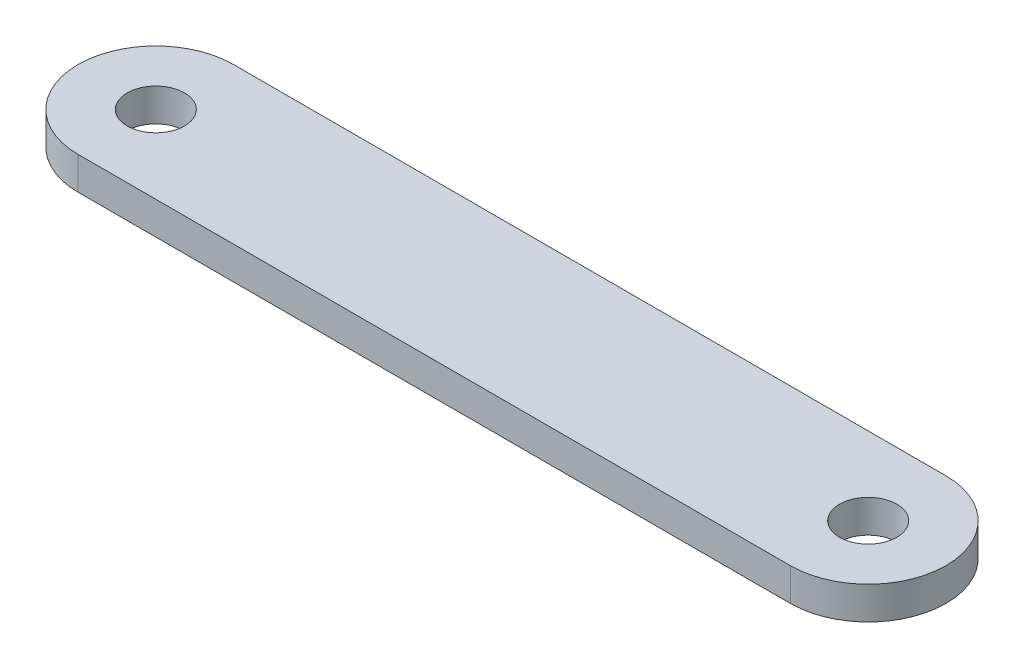
SolidWorks part; units mm, degrees
ref_plane "Front Plane" through (0, 0, 0) normal (0, 0, 1) x (1, 0, 0)
ref_plane "Top Plane" through (0, 0, 0) normal (0, 1, 0) x (1, 0, 0)
ref_plane "Right Plane" through (0, 0, 0) normal (1, 0, 0) x (0, 0, -1)
sketch "Sketch1" plane through (0, 0, 0) normal (0, 1, 0) x (1, 0, 0)
  line L0 (0, 0) -> (43.5, 0) construction
  line L1 (0, 4.75) -> (43.5, 4.75)
  line L2 (0, -4.75) -> (43.5, -4.75)
  arc A0 (0, 4.75) -> (0, -4.75) centre (0, 0) ccw
  arc A1 (43.5, -4.75) -> (43.5, 4.75) centre (43.5, 0) ccw
  circle A2 centre (0, 0) radius 1.75
  circle A3 centre (43.5, 0) radius 1.75
  point P3 (21.75, 0)
  dimension "D2" = 4.75
  dimension "D3" = 3.5
  dimension "D1" = 43.5
extrude "Boss-Extrude1" add sketch "Sketch1" along normal blind 2
